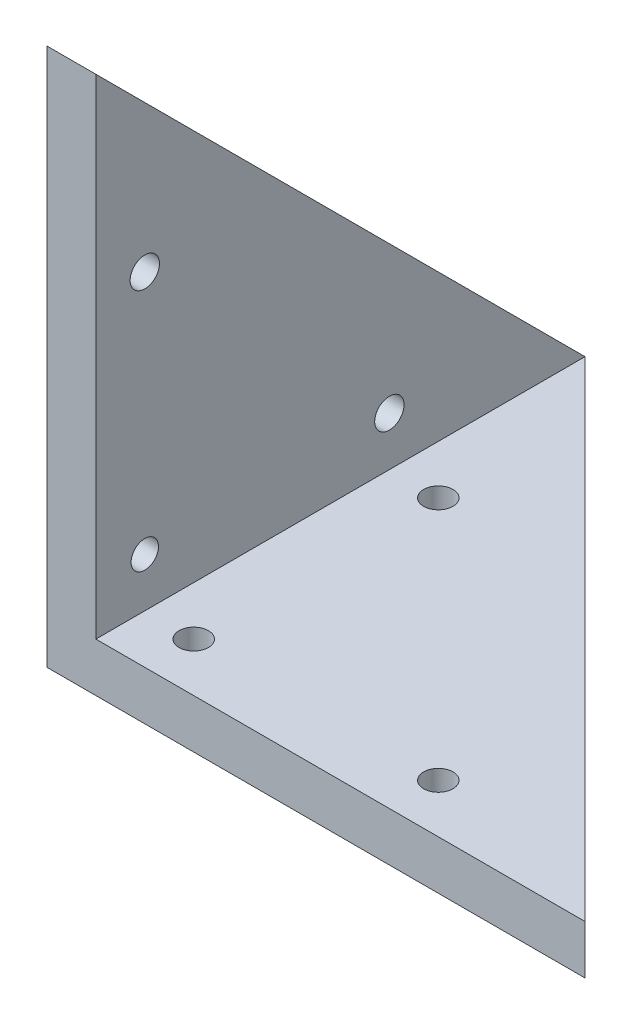
SolidWorks part; units mm, degrees
ref_plane "前视基准面" through (0, 0, 0) normal (0, 0, 1) x (1, 0, 0)
ref_plane "上视基准面" through (0, 0, 0) normal (0, 1, 0) x (1, 0, 0)
ref_plane "右视基准面" through (0, 0, 0) normal (1, 0, 0) x (0, 0, -1)
sketch "草图1" plane through (0, 0, 0) normal (0, 0, 1) x (1, 0, 0)
  line L5 (0, 50) -> (50, 0)
  line L6 (0, 50) -> (-5, 50)
  line L7 (-5, 50) -> (-5, -5)
  line L8 (-5, -5) -> (50, -5)
  line L9 (50, -5) -> (50, 0)
  dimension "D1" = 55
  dimension "D2" = 55
  dimension "D3" = 5
  dimension "D4" = 5
extrude "凸台-拉伸1" add sketch "草图1" along normal blind 5
sketch "草图2" plane through (0, 0, 0) normal (1, 0, 0) x (0, 0, -1)
  line L0 (0, 0) -> (50, 0)
  line L1 (50, 0) -> (0, 50)
  line L2 (0, 50) -> (0, 0)
  dimension "D1" = 50
  dimension "D2" = 50
extrude "凸台-拉伸2" add sketch "草图2" against normal blind 5 separate body
sketch "草图4" plane through (0, 0, 0) normal (0, 0, 1) x (1, 0, 0)
  line L1 (-5, 0) -> (0, 0)
  line L2 (-5, 0) -> (-5, -5)
  line L3 (-5, -5) -> (0, -5)
  line L4 (0, 0) -> (0, -5)
extrude "凸台-拉伸4" add sketch "草图4" against normal blind 50
sketch "草图7" plane through (0, -5, 0) normal (0, -1, 0) x (1, 0, 0)
  line L0 (50, 0) -> (0, 0)
  line L1 (0, 0) -> (0, -50)
  line L2 (0, -50) -> (50, 0)
  dimension "D1" = 50
extrude "凸台-拉伸13" add sketch "草图7" against normal blind 5
sketch "草图8" plane through (0, 0, 0) normal (1, 0, 0) x (0, 0, -1)
  line L0 (0, 0) -> (50, 0) construction
  line L2 (5, 30) -> (5, 5) construction
  line L3 (5, 5) -> (30, 5) construction
  line L5 (5, 30) -> (30, 5) construction
  line L7 (0, 0) -> (0, 50) construction
  circle A0 centre (5, 30) radius 1.5
  circle A1 centre (5, 5) radius 1.4
  circle A2 centre (30, 5) radius 1.5
  point P0 (18.9005, 16.0995)
  dimension "D1" = 25
  dimension "D2" = 25
  dimension "D3" = 5
  dimension "D4" = 5
extrude "切除-拉伸1" cut sketch "草图8" against normal through all
sketch "草图9" plane through (0, 0, 0) normal (0, 0, -1) x (-1, 0, 0)
  line L0 (0, 0) -> (0, 50) construction
  line L1 (-30, 5) -> (-5, 5) construction
  line L4 (-5, 5) -> (-5, 30) construction
  line L5 (-30, 5) -> (-5, 30) construction
  line L7 (-50, 0) -> (0, 0) construction
  circle A0 centre (-5, 30) radius 1.5
  circle A1 centre (-5, 5) radius 1.5
  circle A2 centre (-30, 5) radius 1.5
  point P0 (-20.4255, 14.5745)
  dimension "D1" = 25
  dimension "D2" = 25
  dimension "D3" = 5
  dimension "D4" = 5
extrude "切除-拉伸2" cut sketch "草图9" against normal through all
sketch "草图10" plane through (0, 0, 0) normal (0, 1, 0) x (1, 0, 0)
  line L0 (50, 0) -> (0, 0) construction
  line L1 (5, 5) -> (30, 5) construction
  line L2 (5, 5) -> (5, 30) construction
  line L5 (0, 50) -> (0, 0) construction
  circle A0 centre (5, 30) radius 1.5
  circle A1 centre (5, 5) radius 1.5
  circle A2 centre (30, 5) radius 1.5
  dimension "D1" = 25
  dimension "D2" = 25
  dimension "D3" = 5
  dimension "D4" = 5
extrude "切除-拉伸3" cut sketch "草图10" against normal through all
sketch "草图11" plane through (0, 0, 5) normal (0, 0, 1) x (1, 0, 0)
  line L0 (-5, 50) -> (-5, -5)
  line L1 (-5, -5) -> (50, -5)
  line L2 (50, -5) -> (50, 0)
  line L3 (50, 0) -> (0, 50)
  line L4 (0, 50) -> (-5, 50)
extrude "切除-拉伸4" cut sketch "草图11" against normal blind 5
